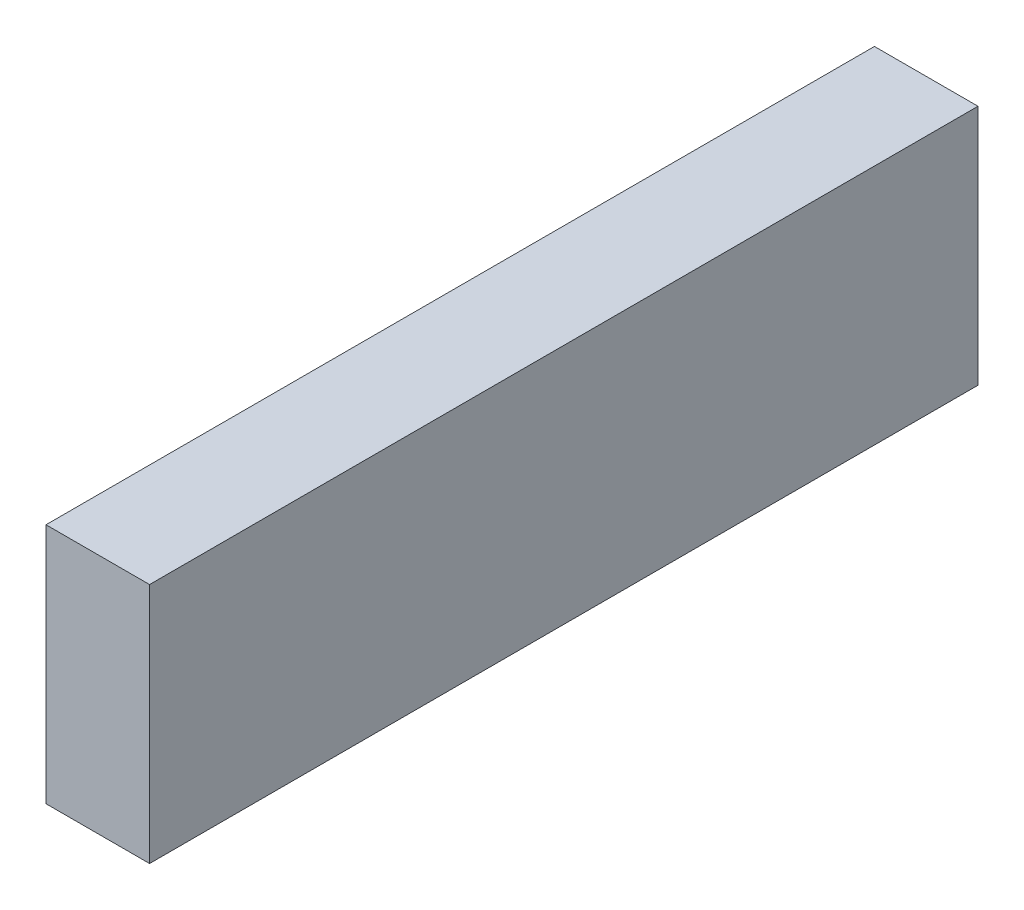
SolidWorks part; units mm, degrees
ref_plane "Front Plane" through (0, 0, 0) normal (0, 0, 1) x (1, 0, 0)
ref_plane "Top Plane" through (0, 0, 0) normal (0, 1, 0) x (1, 0, 0)
ref_plane "Right Plane" through (0, 0, 0) normal (1, 0, 0) x (0, 0, -1)
sketch "Sketch1" plane through (0, 0, 0) normal (0, 0, 1) x (1, 0, 0)
  line L1 (0, 0) -> (38.1, 0)
  line L2 (0, 0) -> (0, 88.9)
  line L3 (0, 88.9) -> (38.1, 88.9)
  line L4 (38.1, 0) -> (38.1, 88.9)
  dimension "D1" = 88.9
  dimension "D2" = 38.1
extrude "Boss-Extrude1" add sketch "Sketch1" along normal blind 304.8
